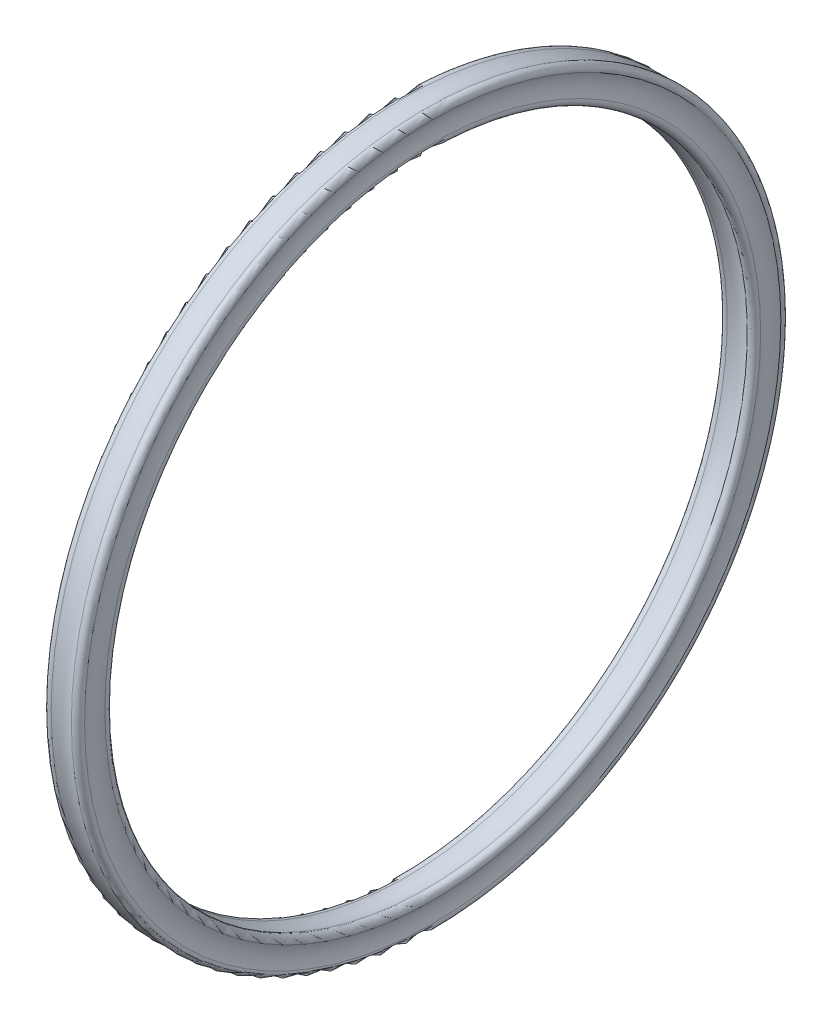
SolidWorks part; units mm, degrees
ref_plane "Front Plane" through (0, 0, 0) normal (0, 0, 1) x (1, 0, 0)
ref_plane "Top Plane" through (0, 0, 0) normal (0, 1, 0) x (1, 0, 0)
ref_plane "Right Plane" through (0, 0, 0) normal (1, 0, 0) x (0, 0, -1)
sketch "Sketch1" plane through (0, 0, 0) normal (0, 0, 1) x (1, 0, 0)
  line L0 (-1.3081, 0) -> (1.3081, 0) construction
  line L1 (-1.3081, 27.0637) -> (1.3081, 27.0637) construction
  line L2 (-1.3081, 27.0637) -> (-1.3081, 24.4475) construction
  line L3 (-1.3081, 24.4475) -> (1.3081, 24.4475) construction
  line L4 (1.3081, 27.0637) -> (1.3081, 24.4475) construction
  line L5 (-1.3081, 24.4475) -> (1.3081, 27.0637) construction
  line L9 (1.1119, 25.7556) -> (1.1119, 24.4475) construction
  line L11 (1.3081, 24.4475) -> (1.3081, -24.4475) construction
  line L12 (-1.3081, 27.0637) -> (-1.3081, -27.0637) construction
  circle A0 centre (0, 25.7556) radius 1.1119 construction
  arc A1 (-1.2751, 26.525) -> (-1.2751, 24.9862) centre (-3.007, 25.7556) cw
  arc A2 (-0.7694, 27.0307) -> (0.7694, 27.0307) centre (0, 28.7626) ccw
  arc A3 (-1.2751, 26.525) -> (-0.7694, 27.0307) centre (-0.925, 26.6806) cw
  arc A4 (1.2751, 26.525) -> (1.2751, 24.9862) centre (3.007, 25.7556) ccw
  arc A5 (-0.7694, 24.4805) -> (0.7694, 24.4805) centre (0, 22.7486) cw
  arc A6 (0.7694, 27.0307) -> (1.2751, 26.525) centre (0.925, 26.6806) cw
  arc A7 (-1.2751, 24.9862) -> (-0.7694, 24.4805) centre (-0.925, 24.8306) ccw
  arc A8 (0.7694, 24.4805) -> (1.2751, 24.9862) centre (0.925, 24.8306) ccw
  circle A9 centre (0, 25.7556) radius 1.3081 construction
  dimension "D1" = 2.2238
revolve "Revolve1" add sketch "Sketch1" angle 360 mid plane about L0
equation "\"D1@Sketch1\" = \"Width@Sketch1\"*.85"
